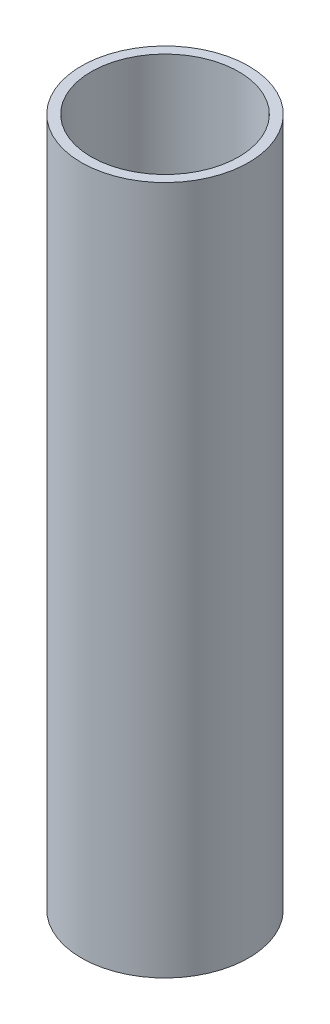
SolidWorks part; units mm, degrees
material "ABS"
ref_plane "Front Plane" through (0, 0, 0) normal (0, 0, 1) x (1, 0, 0)
ref_plane "Top Plane" through (0, 0, 0) normal (0, 1, 0) x (1, 0, 0)
ref_plane "Right Plane" through (0, 0, 0) normal (1, 0, 0) x (0, 0, -1)
sketch "Sketch1" plane through (0, 0, 0) normal (0, 1, 0) x (1, 0, 0)
  circle A0 centre (0, 0) radius 7.5
  circle A1 centre (0, 0) radius 8.5
  dimension "D1" = 17
  dimension "D2" = 15
extrude "Boss-Extrude1" add sketch "Sketch1" along normal blind 70
